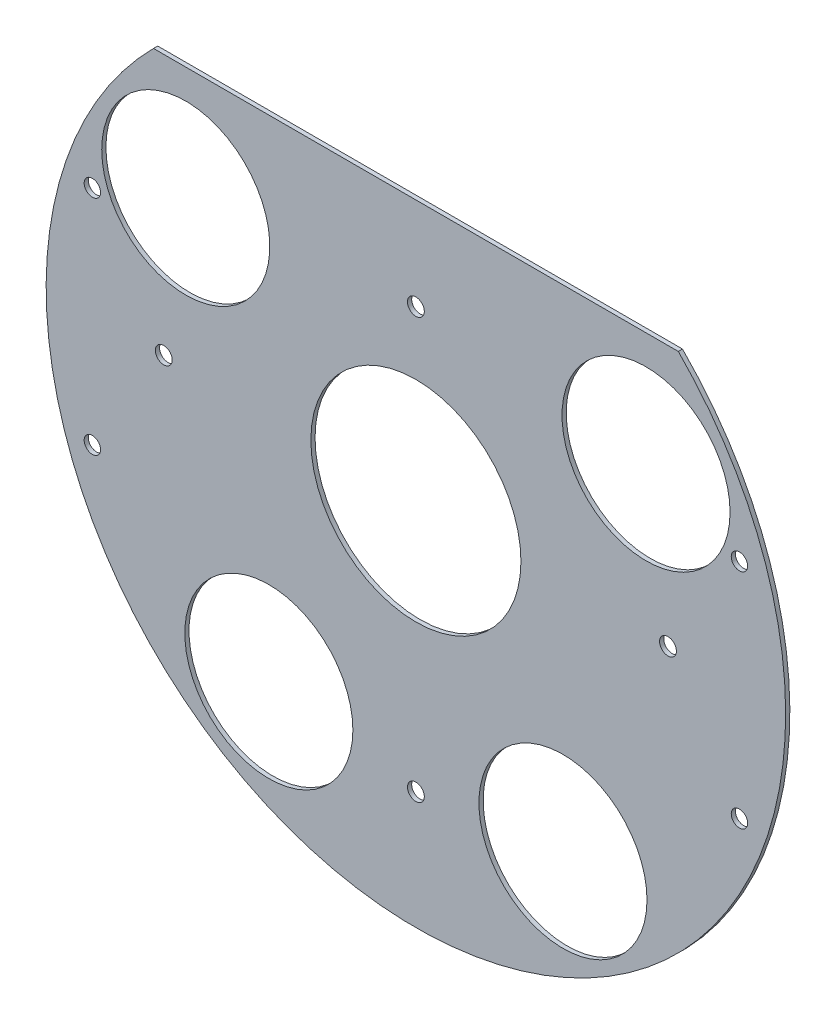
SolidWorks part; units mm, degrees
material "2A12"
ref_plane "前视基准面" through (0, 0, 0) normal (0, 0, 1) x (1, 0, 0)
ref_plane "上视基准面" through (0, 0, 0) normal (0, 1, 0) x (1, 0, 0)
ref_plane "右视基准面" through (0, 0, 0) normal (1, 0, 0) x (0, 0, -1)
sketch "草图1" plane through (0, 0, 0) normal (0, 0, 1) x (1, 0, 0)
  line L0 (-62.45, 62) -> (62.45, 62)
  line L1 (0, 0) -> (0, 62) construction
  line L2 (-35, -54.7723) -> (35, -54.7723) construction
  arc A0 (-62.45, 62) -> (62.45, 62) centre (0, 0) ccw
  circle A1 centre (0, 0) radius 25
  circle A2 centre (54.772, 35) radius 20
  circle A3 centre (-54.772, 35) radius 20
  circle A4 centre (35, -54.7723) radius 20
  circle A5 centre (-35, -54.7723) radius 20
  dimension "D1" = 176
  dimension "D2" = 50
  dimension "D4" = 40
  dimension "D5" = 35
  dimension "D6" = 54.772
  dimension "D7" = 35
  dimension "D8" = 65
  dimension "D9" = 35
  dimension "D3" = 62
extrude "凸台-拉伸1" add sketch "草图1" along normal blind 1
hole_wizard "Ø3.9 (3.9) 直径孔1" positions "草图3" profile "草图2" hole size "Ø3.9" standard "GB" end condition through all
sketch "草图3" plane through (0, 0, 0) normal (0, 0, -1) x (-1, 0, 0)
  point P0 (-77, 26)
  point P2 (-77, -27)
  point P4 (77, -27)
  point P6 (77, 26)
sketch "草图2" plane through (77, 26, 0) normal (1, 0, 0) x (0, 1, 0)
  line L0 (0, 0) -> (0, 1)
  line L1 (0, 1) -> (1.95, 1)
  line L2 (1.95, 1) -> (1.95, 0)
  line L5 (1.95, 0) -> (0, 0)
  line L11 (0, -6.35) -> (0, 107.95) construction
  dimension "通孔孔直径" = 3.9
  dimension "通孔孔深度" = 1
sketch "草图4" plane through (0, 0, 1) normal (0, 0, 1) x (1, 0, 0)
  circle A0 centre (-60, 0) radius 2
  circle A1 centre (0, 40) radius 2
  circle A2 centre (60, 0) radius 2
  circle A3 centre (0, -60) radius 2
  dimension "D1" = 40
  dimension "D3" = 60
  dimension "D5" = 4
  dimension "D6" = 4
  dimension "D7" = 4
  dimension "D8" = 4
  dimension "D2" = 60
  dimension "D4" = 60
extrude "切除-拉伸1" cut sketch "草图4" against normal blind 10
